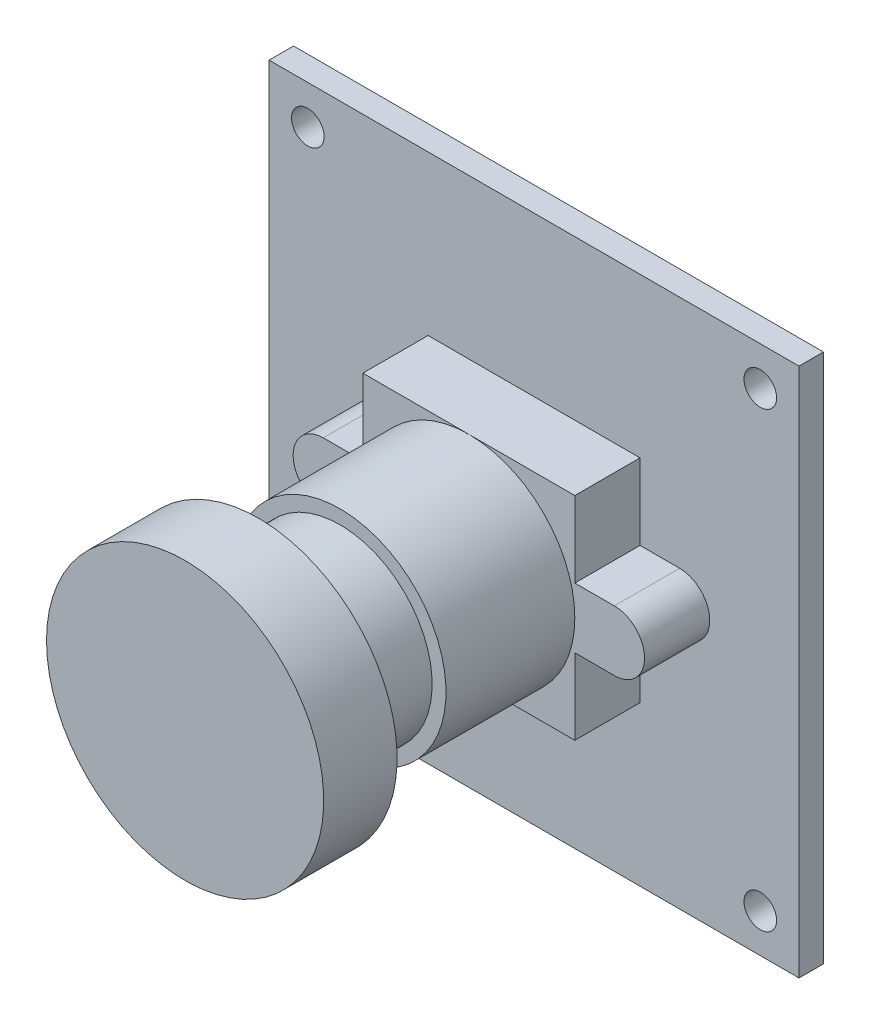
SolidWorks part; units mm, degrees
ref_plane "Front Plane" through (0, 0, 0) normal (0, 0, 1) x (1, 0, 0)
ref_plane "Top Plane" through (0, 0, 0) normal (0, 1, 0) x (1, 0, 0)
ref_plane "Right Plane" through (0, 0, 0) normal (1, 0, 0) x (0, 0, -1)
sketch "Sketch2" plane through (0, 0, 0) normal (0, 0, 1) x (1, 0, 0)
  line L1 (16.25, -16.25) -> (-16.25, -16.25)
  line L2 (16.25, -16.25) -> (16.25, 16.25)
  line L3 (16.25, 16.25) -> (-16.25, 16.25)
  line L4 (-16.25, -16.25) -> (-16.25, 16.25)
  line L5 (16.25, -16.25) -> (-16.25, 16.25) construction
  line L6 (16.25, 16.25) -> (-16.25, -16.25) construction
  line L7 (13.875, -13.875) -> (-13.875, -13.875) construction
  line L8 (13.875, -13.875) -> (13.875, 13.875) construction
  line L9 (13.875, 13.875) -> (-13.875, 13.875) construction
  line L10 (-13.875, -13.875) -> (-13.875, 13.875) construction
  line L11 (13.875, -13.875) -> (-13.875, 13.875) construction
  line L12 (13.875, 13.875) -> (-13.875, -13.875) construction
  circle A0 centre (13.875, 13.875) radius 1
  circle A1 centre (13.875, -13.875) radius 1
  circle A2 centre (-13.875, -13.875) radius 1
  circle A3 centre (-13.875, 13.875) radius 1
  point P0 (0, 0)
  point P6 (0, 0)
  dimension "D4" = 2
  dimension "D1" = 32.5
  dimension "D2" = 32.5
  dimension "D3" = 27.75
extrude "Boss-Extrude1" add sketch "Sketch2" along normal blind 1.5
sketch "Sketch4" plane through (0, 0, 1.5) normal (0, 0, 1) x (1, 0, 0)
  line L0 (8.925, 0) -> (-8.925, 0) construction
  line L1 (6.5, -6.5) -> (-6.5, -6.5)
  line L2 (6.5, -6.5) -> (6.5, 6.5)
  line L3 (6.5, 6.5) -> (-6.5, 6.5)
  line L4 (-6.5, -6.5) -> (-6.5, 6.5)
  line L5 (6.5, -6.5) -> (-6.5, 6.5) construction
  line L6 (6.5, 6.5) -> (-6.5, -6.5) construction
  line L7 (8.925, -1.85) -> (-8.925, -1.85)
  line L8 (8.925, 1.85) -> (-8.925, 1.85)
  arc A0 (8.925, -1.85) -> (8.925, 1.85) centre (8.925, 0) ccw
  arc A1 (-8.925, 1.85) -> (-8.925, -1.85) centre (-8.925, 0) ccw
  point P0 (0, 0)
  point P8 (0, 0)
  dimension "D4" = 1.85
  dimension "D1" = 13
  dimension "D2" = 13
  dimension "D3" = 17.85
extrude "Boss-Extrude2" add sketch "Sketch4" along normal blind 4 contours L2 L1 L4 L3 | L8 A1 L7 A0
sketch "Sketch5" plane through (0, 0, 0) normal (0, 1, 0) x (1, 0, 0)
  line L0 (0, 0) -> (0, -25.1637) construction
  line L1 (0, -5.5) -> (6.5, -5.5)
  line L2 (6.5, -5.5) -> (-6.5, -5.5) construction
  line L3 (6.5, -5.5) -> (6.5, -13.4)
  line L4 (6.5, -13.4) -> (5.65, -13.4)
  line L5 (5.65, -13.4) -> (5.65, -18.4)
  line L6 (5.65, -18.4) -> (8.5, -18.4)
  line L7 (8.5, -18.4) -> (8.5, -22.9)
  line L8 (8.5, -22.9) -> (0, -22.9)
  line L9 (0, -5.5) -> (0, -22.9)
  dimension "D1" = 13
  dimension "D2" = 7.9
  dimension "D3" = 5
  dimension "D4" = 11.3
  dimension "D5" = 17
  dimension "D6" = 4.5
revolve "Revolve1" add sketch "Sketch5" angle 360 about L0
sketch "Sketch6" plane through (0, 0, 0) normal (0, 0, -1) x (-1, 0, 0)
  line L0 (-13.875, -13.875) -> (13.875, -13.875) construction
  line L1 (5, -16.25) -> (-5, -16.25)
  line L2 (5, -16.25) -> (5, -11.5)
  line L3 (5, -11.5) -> (-5, -11.5)
  line L4 (-5, -16.25) -> (-5, -11.5)
  line L5 (5, -16.25) -> (-5, -11.5) construction
  line L6 (5, -11.5) -> (-5, -16.25) construction
  point P0 (0, -13.875)
  dimension "D1" = 10
  dimension "D2" = 4.75
extrude "Boss-Extrude3" add sketch "Sketch6" along normal blind 6
